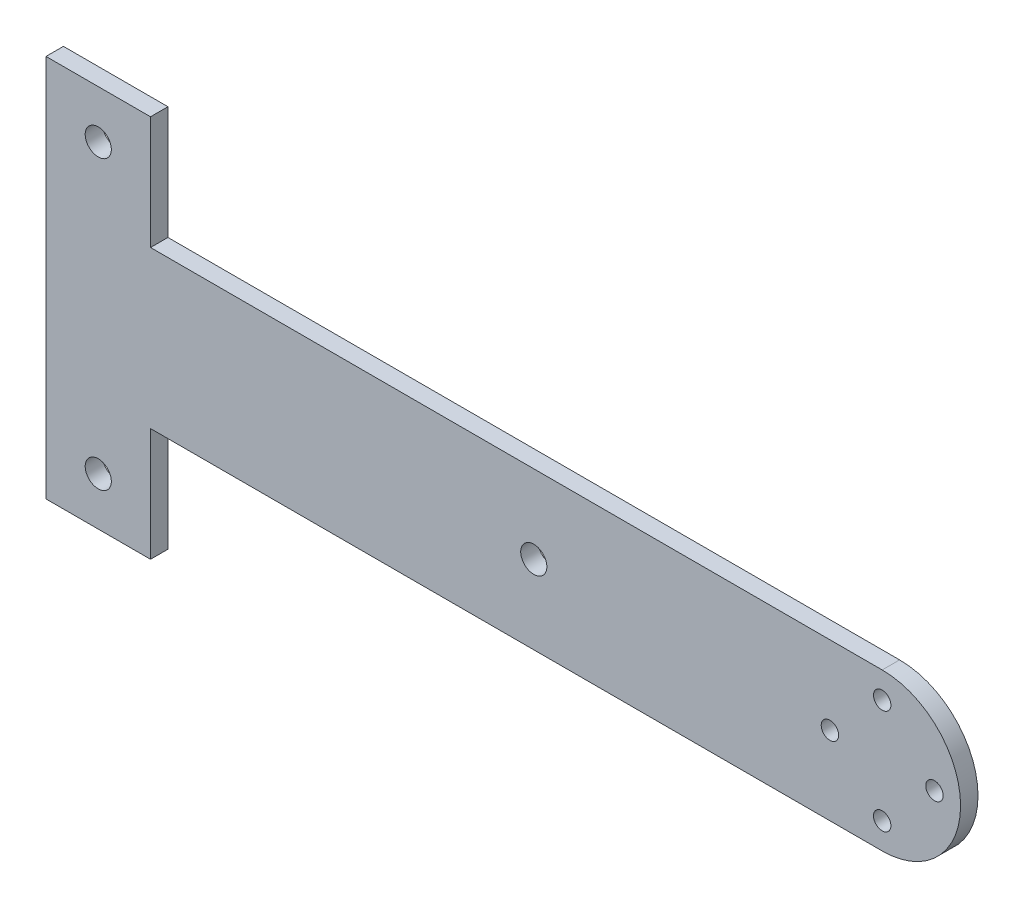
SolidWorks part; units mm, degrees
ref_plane "前视基准面" through (0, 0, 0) normal (0, 0, 1) x (1, 0, 0)
ref_plane "上视基准面" through (0, 0, 0) normal (0, 1, 0) x (1, 0, 0)
ref_plane "右视基准面" through (0, 0, 0) normal (1, 0, 0) x (0, 0, -1)
sketch "草图1" plane through (0, 0, 0) normal (0, 0, 1) x (1, 0, 0)
  line L0 (41.2764, 0.1457) -> (41.2764, 6.1457)
  line L1 (41.2764, -8.8543) -> (-42.7236, -8.8543)
  line L2 (41.2764, 9.1457) -> (-42.7236, 9.1457)
  line L3 (-42.7236, 9.1457) -> (-42.7236, 22.1457)
  line L4 (-42.7236, 22.1457) -> (-54.7236, 22.1457)
  line L5 (-54.7236, 22.1457) -> (-54.7236, -21.8543)
  line L6 (-54.7236, -21.8543) -> (-42.7236, -21.8543)
  line L7 (-42.7236, -21.8543) -> (-42.7236, -8.8543)
  circle A1 centre (1.2764, 0.1457) radius 1.5
  circle A2 centre (-48.7236, 16.6457) radius 1.5
  circle A3 centre (-48.7236, -16.3543) radius 1.5
  circle A4 centre (41.2764, 6.1457) radius 1
  circle A5 centre (47.2764, 0.1457) radius 1
  circle A6 centre (41.2764, -5.8543) radius 1
  circle A7 centre (35.2764, 0.1457) radius 1
  circle A8 centre (41.2764, 0.1457) radius 9 construction
  arc A9 (41.2764, 9.1457) -> (41.2764, -8.8543) centre (41.2764, 0.1457) cw
  dimension "D1" = 3
  dimension "D3" = 2
  dimension "D5" = 33
  dimension "D2" = 6
  dimension "D6" = 13
  dimension "D7" = 12
  dimension "D8" = 90
  dimension "D9" = 6
  dimension "D4" = 4
extrude "凸台-拉伸1" add sketch "草图1" along normal blind 2
